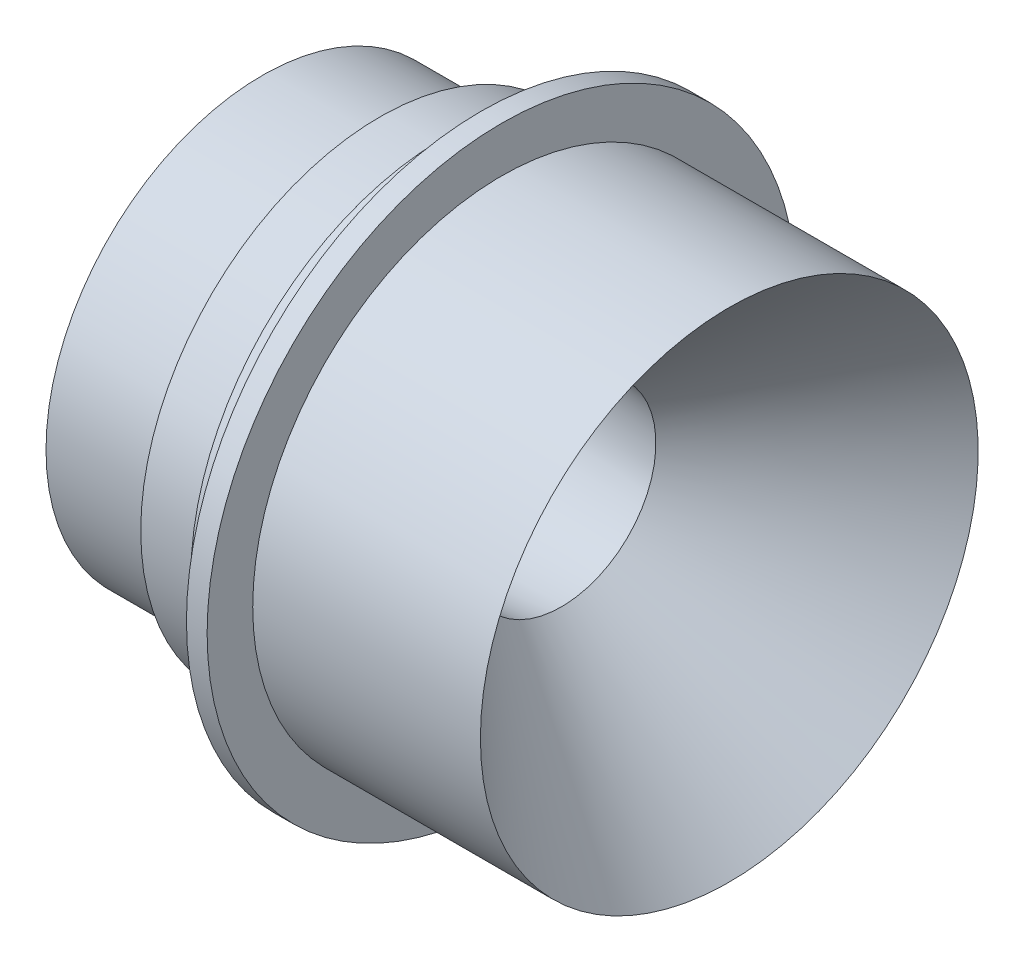
SolidWorks part; units mm, degrees
ref_plane "Front Plane" through (0, 0, 0) normal (0, 0, 1) x (1, 0, 0)
ref_plane "Top Plane" through (0, 0, 0) normal (0, 1, 0) x (1, 0, 0)
ref_plane "Right Plane" through (0, 0, 0) normal (1, 0, 0) x (0, 0, -1)
sketch "Sketch1" plane through (0, 0, 0) normal (0, 0, 1) x (1, 0, 0)
  line L0 (-46.1574, 0) -> (51.9725, 0) construction
  line L1 (-36.5499, 18.9713) -> (-36.5499, 36.1315)
  line L2 (-36.5499, 36.1315) -> (-16.9001, 36.1315)
  line L3 (-16.9001, 36.1315) -> (-16.9001, 39.9477)
  line L4 (-16.9001, 39.9477) -> (-6.1785, 39.9477)
  line L5 (-6.1785, 39.9477) -> (-6.1785, 42.2882)
  line L6 (-6.1785, 42.2882) -> (0, 42.2882)
  line L7 (0, 42.2882) -> (0, 49.2125)
  line L8 (0, 49.2125) -> (3.4551, 49.2125)
  line L9 (3.4551, 49.2125) -> (3.4551, 41.5925)
  line L10 (3.4551, 41.5925) -> (41.5027, 41.5925)
  line L11 (41.5027, 41.5925) -> (13.4474, 15.788)
  line L12 (13.4474, 15.788) -> (-36.5499, 18.9713)
  point P3 (13.4474, 15.2646)
  point P5 (-35.0723, 18.3539)
  dimension "D1" = 49.2125
  dimension "D2" = 40.005
  dimension "D3" = 41.5925
  dimension "D4" = 36.1315
revolve "Revolve1" add sketch "Sketch1" angle 360 about L0
